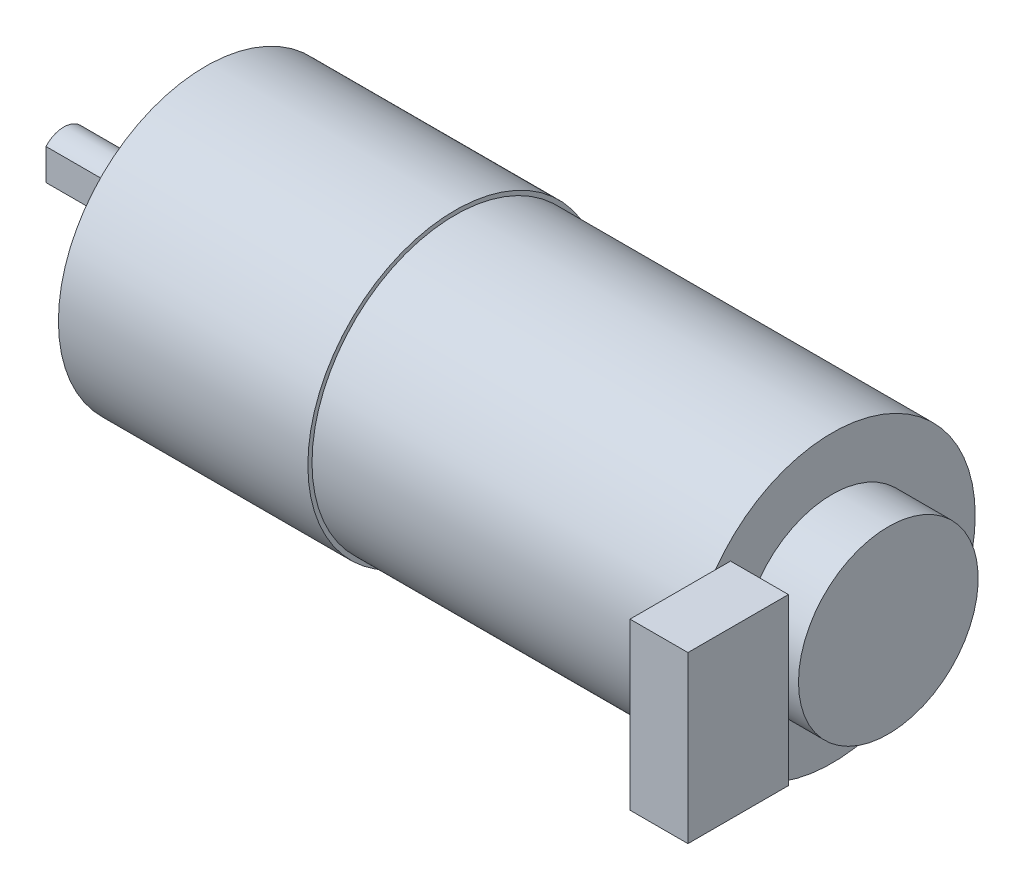
SolidWorks part; units mm, degrees
ref_plane "Front Plane" through (0, 0, 0) normal (0, 0, 1) x (1, 0, 0)
ref_plane "Top Plane" through (0, 0, 0) normal (0, 1, 0) x (1, 0, 0)
ref_plane "Right Plane" through (0, 0, 0) normal (1, 0, 0) x (0, 0, -1)
sketch "Sketch1" plane through (0, 0, 0) normal (0, 1, 0) x (1, 0, 0)
  line L13 (4.75, 19.7) -> (4.75, 4.5)
  line L21 (-53, -0.35) -> (-31.9, -0.35)
  line L25 (-31.9, 24.2) -> (-31.9, 24.55)
  line L26 (-31.9, 24.55) -> (-53, 24.55)
  line L29 (4.75, 4.5) -> (0, 4.5)
  line L31 (0, 4.5) -> (0, 0)
  line L32 (0, 0) -> (-31.9, 0)
  line L33 (-31.9, -0.35) -> (-31.9, 0)
  line L34 (-31.9, 24.2) -> (0, 24.2)
  line L35 (0, 24.2) -> (0, 19.7)
  line L36 (0, 19.7) -> (4.75, 19.7)
  line L37 (-53, -0.35) -> (-53, 8.6)
  line L38 (-53, 8.6) -> (-55.5, 8.6)
  line L39 (-55.5, 8.6) -> (-55.5, 10.1)
  line L40 (-55.5, 10.1) -> (-65, 10.1)
  line L41 (-65, 10.1) -> (-65, 14.1)
  line L42 (-65, 14.1) -> (-55.5, 14.1)
  line L43 (-55.5, 14.1) -> (-55.5, 15.6)
  line L44 (-55.5, 15.6) -> (-53, 15.6)
  line L45 (-53, 15.6) -> (-53, 24.55)
  line L46 (-65, 12.1) -> (4.75, 12.1) construction
  dimension "D1" = 15.2
  dimension "D2" = 24.2
  dimension "D3" = 4.5
  dimension "D4" = 31.9
  dimension "D5" = 31.9
  dimension "D6" = 21.1
  dimension "D7" = 21.1
  dimension "D8" = 4
  dimension "D9" = 12
  dimension "D10" = 2.5
  dimension "D11" = 2.5
  dimension "D12" = 7
  dimension "D13" = 8.95
  dimension "D14" = 8.95
  dimension "D15" = 1.5
  dimension "D16" = 0.35
  dimension "D17" = 4.75
  dimension "D18" = 69.75
revolve "Revolve5" add sketch "Sketch1" angle 360 about L46
sketch "Sketch2" plane through (-65, 0, 0) normal (-1, 0, 0) x (0, 0, 1)
  line L0 (-10.1, 0) -> (-10.6, 0)
  line L1 (-10.6, 0) -> (-10.6, 1.3229)
  line L2 (-10.6, 1.3229) -> (-10.6, -1.3229)
  circle A0 centre (-12.1, 0) radius 2
  circle M3 centre (-12.1, 0) radius 2
  dimension "D2" = 4
  dimension "D1" = 0.5
extrude "Cut-Extrude1" cut sketch "Sketch2" against normal blind 8 contours L1 L0 M3 | L0 L2 M3 | A0
sketch "Sketch4" plane through (0, 0, 0) normal (1, 0, 0) x (0, 0, -1)
  line L0 (3.5, -7) -> (3.5, 7)
  line L5 (-5, -7) -> (3.5, -7)
  line L6 (-5, -7) -> (-5, 7)
  line L7 (-5, 7) -> (3.5, 7)
  line L8 (3.5, -7) -> (3.5, 7)
  line L11 (-5, 7) -> (-5, -7)
  line L12 (-5, -7) -> (3.5, -7)
  point P0 (0, 0)
  circle M6 centre (12.1, 0) radius 12.1
  dimension "D1" = 14
  dimension "D2" = 8.5
  dimension "D3" = 5
  dimension "D4" = 7
extrude "Boss-Extrude1" add sketch "Sketch4" along normal blind 4.9 contours L7 L6 L5 M6 | L7 L5 L0 M6
